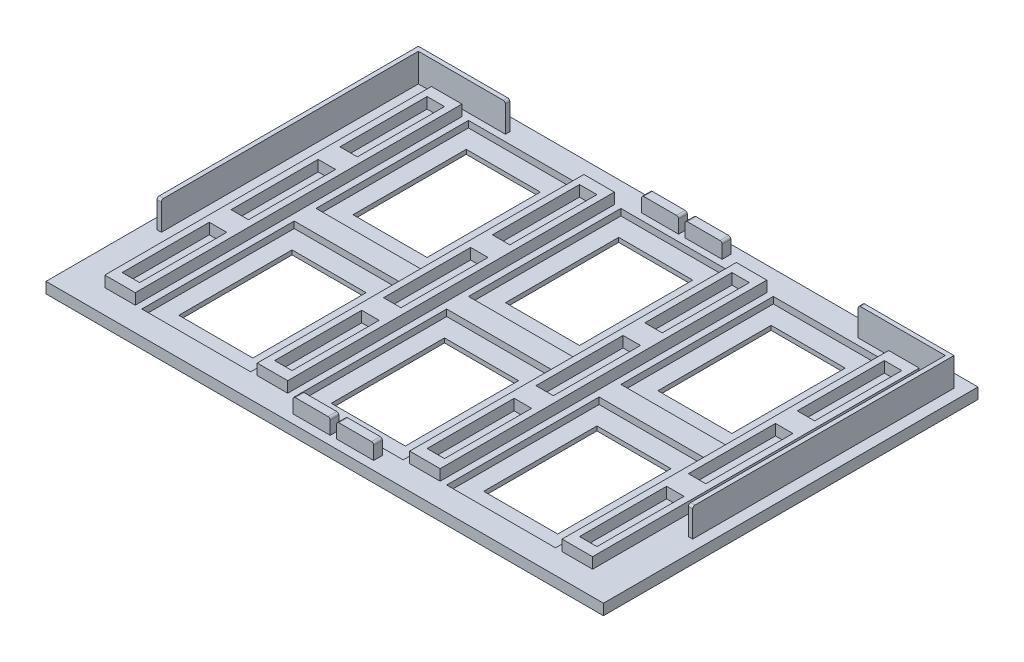
SolidWorks part; units mm, degrees
ref_plane "Front Plane" through (0, 0, 0) normal (0, 0, 1) x (1, 0, 0)
ref_plane "Top Plane" through (0, 0, 0) normal (0, 1, 0) x (1, 0, 0)
ref_plane "Right Plane" through (0, 0, 0) normal (1, 0, 0) x (0, 0, -1)
sketch "Sketch2" plane through (0, 0, 0) normal (0, 1, 0) x (1, 0, 0)
  line L2 (-64, 43) -> (64, 43)
  line L3 (64, 43) -> (64, -43)
  line L4 (-64, 43) -> (-64, -43)
  line L5 (-64, -43) -> (64, -43)
  point P4 (0, 0)
  point P8 (0, 0)
  dimension "D1" = 128
  dimension "D2" = 86
extrude "Boss-Extrude1" add sketch "Sketch2" against normal blind 2.5
sketch "Sketch3" plane through (0, 0, 0) normal (0, 1, 0) x (1, 0, 0)
  line L1 (-12.5, 37.5) -> (12.5, 37.5)
  line L2 (-12.5, 37.5) -> (-12.5, 2.5)
  line L3 (-12.5, -2.5) -> (12.5, -2.5)
  line L5 (-12.5, 37.5) -> (-12.5, 2.5)
  line L6 (-12.5, 2.5) -> (12.5, 2.5)
  line L8 (12.5, 37.5) -> (12.5, 2.5)
  line L13 (12.5, -37.5) -> (12.5, -2.5)
  line L14 (-12.5, -37.5) -> (12.5, -37.5)
  line L19 (-12.5, -37.5) -> (-12.5, -2.5)
  line L54 (47.5, -37.5) -> (22.5, -37.5)
  line L63 (22.5, -37.5) -> (22.5, -2.5)
  line L64 (47.5, -2.5) -> (22.5, -2.5)
  line L73 (47.5, -37.5) -> (47.5, -2.5)
  line L74 (47.5, 37.5) -> (47.5, 2.5)
  line L75 (47.5, 2.5) -> (22.5, 2.5)
  line L76 (22.5, 37.5) -> (22.5, 2.5)
  line L77 (47.5, 37.5) -> (22.5, 37.5)
  line L78 (-47.5, -37.5) -> (-47.5, -2.5)
  line L79 (-47.5, -2.5) -> (-22.5, -2.5)
  line L80 (-22.5, -37.5) -> (-22.5, -2.5)
  line L81 (-47.5, -37.5) -> (-22.5, -37.5)
  line L82 (-47.5, 37.5) -> (-22.5, 37.5)
  line L83 (-22.5, 37.5) -> (-22.5, 2.5)
  line L84 (-47.5, 2.5) -> (-22.5, 2.5)
  line L85 (-47.5, 37.5) -> (-47.5, 2.5)
  point P3 (0, 0)
  point P17 (0, 0)
  dimension "D2" = 75
  dimension "D3" = 35
sketch "Sketch9" plane through (0, 0, 0) normal (0, 1, 0) x (1, 0, 0)
  line L0 (-61.5, -20) -> (-60.5, -20)
  line L4 (-40.5, 40) -> (-40.5, 39)
  line L7 (-61.5, 40) -> (-61.5, -20)
  line L8 (-60.5, -20) -> (-60.5, 39)
  line L9 (-60.5, 39) -> (-40.5, 39)
  line L11 (-40.5, 40) -> (-61.5, 40)
  line L12 (40.5, 40) -> (61.5, 40)
  line L13 (61.5, 40) -> (61.5, -20)
  line L14 (61.5, -20) -> (60.5, -20)
  line L15 (60.5, -20) -> (60.5, 39)
  line L16 (60.5, 39) -> (40.5, 39)
  line L17 (40.5, 40) -> (40.5, 39)
  line L28 (-0.75, 39) -> (-9.25, 39)
  line L29 (-0.75, 39) -> (-0.75, 41)
  line L30 (-0.75, 41) -> (-9.25, 41)
  line L31 (-9.25, 39) -> (-9.25, 41)
  line L32 (9.25, 41) -> (0.75, 41)
  line L33 (9.25, 41) -> (9.25, 39)
  line L34 (9.25, 39) -> (0.75, 39)
  line L35 (0.75, 41) -> (0.75, 39)
  line L36 (-0.75, -41) -> (-9.25, -41)
  line L37 (-9.25, -39) -> (-9.25, -41)
  line L38 (-0.75, -39) -> (-9.25, -39)
  line L39 (-0.75, -39) -> (-0.75, -41)
  line L40 (9.25, -39) -> (0.75, -39)
  line L41 (0.75, -41) -> (0.75, -39)
  line L42 (9.25, -41) -> (0.75, -41)
  line L43 (9.25, -41) -> (9.25, -39)
  point P3 (0, 40)
  point P9 (0, 0)
  point P12 (0, 0)
  point P17 (0, 39)
  point P32 (0, 39)
  dimension "D5" = 20
  dimension "D1" = 60
  dimension "D4" = 1
  dimension "D6" = 59
  dimension "D7" = 21
extrude "Boss-Extrude3" add sketch "Sketch9" along normal blind 6.5
sketch "Sketch10" plane through (0, 0, 0) normal (0, 1, 0) x (1, 0, 0)
  line L1 (-9.25, 41) -> (-0.75, 41)
  line L2 (-9.25, 41) -> (-9.25, 39)
  line L3 (-9.25, 39) -> (-0.75, 39)
  line L4 (-0.75, 41) -> (-0.75, 39)
  line L5 (0.75, 41) -> (9.25, 41)
  line L6 (0.75, 41) -> (0.75, 39)
  line L7 (0.75, 39) -> (9.25, 39)
  line L8 (9.25, 41) -> (9.25, 39)
  line L9 (-9.25, -39) -> (-0.75, -39)
  line L10 (-9.25, -39) -> (-9.25, -41)
  line L11 (-9.25, -41) -> (-0.75, -41)
  line L12 (-0.75, -39) -> (-0.75, -41)
  line L13 (0.75, -39) -> (9.25, -39)
  line L14 (0.75, -39) -> (0.75, -41)
  line L15 (0.75, -41) -> (9.25, -41)
  line L16 (9.25, -39) -> (9.25, -41)
extrude "Cut-Extrude9" cut sketch "Sketch10" along normal through all from offset 3.5 contours L2 L1 L4 L3 | L6 L5 L8 L7 | L10 L9 L12 L11 | L14 L13 L16 L15
fillet "Fillet1" radius 0.5 12 edges at (-61, 6.5, 20) (-40.5, 6.5, -39.5) (-0.75, 3.5, -40) (-9.25, 3.5, -40) (0.75, 3.5, -40) (9.25, 3.5, -40) (40.5, 6.5, -39.5) (61, 6.5, 20) (9.25, 3.5, 40) (-9.25, 3.5, 40) (-0.75, 3.5, 40) (0.75, 3.5, 40)
extrude "Cut-Extrude10" cut sketch "Sketch3" against normal blind 1.5 contours L82 L85 L84 L83 | L78 L81 L80 L79 | L8 L1 L2 L6 | L19 L14 L13 L3 | L74 L77 L76 L75 | L54 L73 L64 L63
sketch "Sketch11" plane through (0, 0, 0) normal (0, 1, 0) x (1, 0, 0)
  line L1 (-8.5, -7) -> (8.5, -7)
  line L3 (-26.5, -33) -> (-26.5, -7)
  line L4 (-8.5, 33) -> (8.5, 33)
  line L5 (-8.5, 33) -> (-8.5, 7)
  line L10 (-8.5, 7) -> (8.5, 7)
  line L11 (8.5, 33) -> (8.5, 7)
  line L12 (8.5, -33) -> (8.5, -7)
  line L13 (-8.5, -33) -> (8.5, -33)
  line L14 (-8.5, -33) -> (-8.5, -7)
  line L15 (-26.5, -33) -> (-43.5, -33)
  line L16 (-43.5, -33) -> (-43.5, -7)
  line L17 (-26.5, -7) -> (-43.5, -7)
  line L18 (43.5, 7) -> (26.5, 7)
  line L19 (26.5, 33) -> (26.5, 7)
  line L20 (43.5, 33) -> (26.5, 33)
  line L21 (43.5, 33) -> (43.5, 7)
  line L22 (43.5, -33) -> (43.5, -7)
  line L23 (43.5, -33) -> (26.5, -33)
  line L24 (26.5, -33) -> (26.5, -7)
  line L25 (43.5, -7) -> (26.5, -7)
  line L26 (-26.5, 7) -> (-43.5, 7)
  line L27 (-43.5, 33) -> (-43.5, 7)
  line L28 (-26.5, 33) -> (-43.5, 33)
  line L29 (-26.5, 33) -> (-26.5, 7)
  point P9 (0, 20)
  point P14 (0, 20)
extrude "Cut-Extrude11" cut sketch "Sketch11" against normal blind 10
sketch "Sketch12" plane through (0, 0, 0) normal (0, 1, 0) x (1, 0, 0)
  line L4 (-21, -37.5) -> (-21, 37.5)
  line L5 (-21, -37.5) -> (-14, -37.5)
  line L6 (-21, 37.5) -> (-14, 37.5)
  line L7 (-14, -37.5) -> (-14, 37.5)
  line L8 (-21, -37.5) -> (-14, 37.5) construction
  line L9 (-21, 37.5) -> (-14, -37.5) construction
  line L10 (-19.5, 10) -> (-15.5, 10)
  line L11 (-19.5, 10) -> (-19.5, -10)
  line L12 (-15.5, 10) -> (-15.5, -10)
  line L13 (-19.5, -10) -> (-15.5, -10)
  line L14 (-19.5, 10) -> (-15.5, -10) construction
  line L15 (-15.5, 10) -> (-19.5, -10) construction
  line L18 (-15.5, 15) -> (-15.5, 35)
  line L19 (-19.5, 35) -> (-15.5, 35)
  line L20 (-19.5, 15) -> (-19.5, 35)
  line L21 (-19.5, 15) -> (-15.5, 15)
  line L22 (-19.5, -15) -> (-15.5, -15)
  line L23 (-19.5, -15) -> (-19.5, -35)
  line L24 (-19.5, -35) -> (-15.5, -35)
  line L25 (-15.5, -15) -> (-15.5, -35)
  line L31 (-50.5, -15) -> (-50.5, -35)
  line L32 (-50.5, -35) -> (-54.5, -35)
  line L33 (-54.5, -15) -> (-54.5, -35)
  line L34 (-50.5, -15) -> (-54.5, -15)
  line L35 (-54.5, 10) -> (-54.5, -10)
  line L36 (-50.5, -10) -> (-54.5, -10)
  line L37 (-50.5, 10) -> (-50.5, -10)
  line L38 (-50.5, 10) -> (-54.5, 10)
  line L39 (-50.5, 15) -> (-54.5, 15)
  line L40 (-50.5, 15) -> (-50.5, 35)
  line L41 (-50.5, 35) -> (-54.5, 35)
  line L42 (-54.5, 15) -> (-54.5, 35)
  line L43 (-49, 37.5) -> (-56, 37.5)
  line L44 (-56, -37.5) -> (-56, 37.5)
  line L45 (-49, -37.5) -> (-56, -37.5)
  line L46 (-49, -37.5) -> (-49, 37.5)
  line L47 (19.5, -15) -> (19.5, -35)
  line L48 (19.5, -35) -> (15.5, -35)
  line L49 (15.5, -15) -> (15.5, -35)
  line L50 (19.5, -15) -> (15.5, -15)
  line L51 (15.5, 10) -> (15.5, -10)
  line L52 (19.5, -10) -> (15.5, -10)
  line L53 (19.5, 10) -> (19.5, -10)
  line L54 (19.5, 10) -> (15.5, 10)
  line L55 (21, 37.5) -> (14, 37.5)
  line L56 (14, -37.5) -> (14, 37.5)
  line L57 (21, -37.5) -> (14, -37.5)
  line L58 (21, -37.5) -> (21, 37.5)
  line L59 (19.5, 15) -> (15.5, 15)
  line L60 (19.5, 15) -> (19.5, 35)
  line L61 (19.5, 35) -> (15.5, 35)
  line L62 (15.5, 15) -> (15.5, 35)
  line L63 (50.5, -15) -> (54.5, -15)
  line L64 (54.5, -15) -> (54.5, -35)
  line L65 (50.5, -35) -> (54.5, -35)
  line L66 (50.5, -15) -> (50.5, -35)
  line L67 (50.5, 10) -> (54.5, 10)
  line L68 (50.5, 10) -> (50.5, -10)
  line L69 (50.5, -10) -> (54.5, -10)
  line L70 (54.5, 10) -> (54.5, -10)
  line L71 (49, -37.5) -> (49, 37.5)
  line L72 (49, -37.5) -> (56, -37.5)
  line L73 (56, -37.5) -> (56, 37.5)
  line L74 (49, 37.5) -> (56, 37.5)
  line L75 (50.5, 15) -> (50.5, 35)
  line L76 (50.5, 35) -> (54.5, 35)
  line L77 (54.5, 15) -> (54.5, 35)
  line L78 (50.5, 15) -> (54.5, 15)
  dimension "D1" = 7
  dimension "D2" = 4
  dimension "D3" = 20
extrude "Boss-Extrude4" add sketch "Sketch12" along normal blind 2.5
equation "\"2.8.00mm\"=3"
equation "\"mm\"=1.5"
